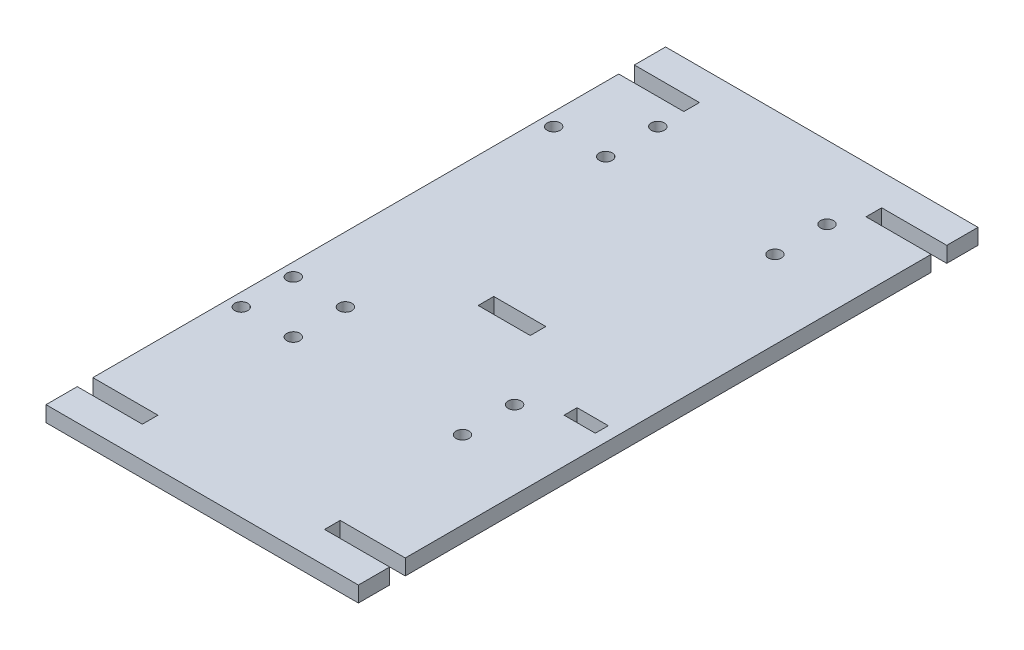
SolidWorks part; units mm, degrees
ref_plane "Front" through (0, 0, 0) normal (0, 0, 1) x (1, 0, 0)
ref_plane "Top" through (0, 0, 0) normal (0, 1, 0) x (1, 0, 0)
ref_plane "Right" through (0, 0, 0) normal (1, 0, 0) x (0, 0, -1)
sketch "Sketch1" plane through (0, 0, 0) normal (0, 1, 0) x (1, 0, 0)
  line L1 (0, 0) -> (-120, 0)
  line L2 (0, 0) -> (0, 238)
  line L3 (0, 238) -> (-120, 238)
  line L4 (-120, 0) -> (-120, 238)
  dimension "D1" = 238
  dimension "D2" = 120
extrude "Boss-Extrude1" add sketch "Sketch1" along normal blind 6
sketch "Sketch2" plane through (0, 6, 0) normal (0, 1, 0) x (1, 0, 0)
  line L0 (-120, 238) -> (-120, 0) construction
  line L1 (-120, 226) -> (-95, 226)
  line L2 (-120, 226) -> (-120, 220)
  line L3 (-120, 220) -> (-95, 220)
  line L4 (-95, 226) -> (-95, 220)
  line L5 (0, 238) -> (-120, 238) construction
  dimension "D1" = 6
  dimension "D2" = 25
  dimension "D3" = 12
extrude "Cut-Extrude1" cut sketch "Sketch2" against normal through all
pattern_linear "LPattern1" count 2 spacing 208 along (0, 0, 1) count 2 spacing 95 along (1, 0, 0) of "Cut-Extrude1"
sketch "Sketch3" plane through (0, 6, 0) normal (0, 1, 0) x (1, 0, 0)
  line L0 (-60, 238) -> (-60, 0) construction
  line L1 (0, 238) -> (-120, 238) construction
  line L2 (-120, 0) -> (0, 0) construction
  line L3 (-120, 119) -> (0, 119) construction
  line L4 (-120, 220) -> (-120, 18) construction
  line L5 (0, 18) -> (0, 220) construction
  line L7 (-70, 116) -> (-50, 116)
  line L8 (-70, 116) -> (-70, 122)
  line L9 (-70, 122) -> (-50, 122)
  line L10 (-50, 116) -> (-50, 122)
  line L11 (-70, 116) -> (-50, 122) construction
  line L12 (-70, 122) -> (-50, 116) construction
  point P12 (-60, 119)
  dimension "D1" = 6
  dimension "D2" = 20
extrude "Cut-Extrude2" cut sketch "Sketch3" against normal blind 10
sketch "Sketch4" plane through (0, 6, 0) normal (0, 1, 0) x (1, 0, 0)
  line L0 (-105, 90) -> (-105, 190) construction
  line L1 (-30, 210) -> (-30, 190) construction
  line L2 (-95, 200) -> (-30, 200) construction
  line L3 (-95, 80) -> (-30, 80) construction
  line L4 (-70, 116) -> (-50, 116) construction
  line L5 (-105, 80) -> (-105, 30) construction
  line L6 (-120, 220) -> (-120, 18) construction
  line L7 (-115, 90) -> (-95, 90) construction
  line L8 (-95, 90) -> (-95, 70) construction
  line L9 (-30, 90) -> (-30, 70) construction
  line L10 (-115, 90) -> (-115, 70) construction
  line L11 (-115, 70) -> (-95, 70) construction
  arc A0 (-105, 90) -> (-95, 80) centre (-95, 90) ccw construction
  arc A1 (-105, 190) -> (-95, 200) centre (-95, 190) cw construction
  circle A2 centre (-30, 210) radius 2.5
  circle A3 centre (-30, 190) radius 2.5
  circle A4 centre (-95, 210) radius 2.5
  circle A5 centre (-95, 190) radius 2.5
  circle A6 centre (-115, 190) radius 2.5
  circle A13 centre (-95, 90) radius 2.5
  circle A14 centre (-115, 90) radius 2.5
  circle A15 centre (-95, 70) radius 2.5
  circle A16 centre (-30, 90) radius 2.5
  circle A17 centre (-30, 70) radius 2.5
  circle A18 centre (-115, 70) radius 2.5
  point P11 (-120, 119)
  point P15 (-105, 200)
  point P17 (-95, 200)
  point P18 (-105, 190)
  point P19 (-105, 90)
  point P20 (-95, 80)
  point P21 (-30, 80)
  point P23 (-30, 200)
  point P26 (-95, 80)
  point P32 (-105, 90)
  point P35 (-95, 190)
  point P39 (-30, 80)
  dimension "D6" = 10
  dimension "D7" = 5
  dimension "D1" = 36
  dimension "D2" = 50
  dimension "D3" = 75
  dimension "D4" = 15
  dimension "D5" = 120
  dimension "D8" = 20
  dimension "D9" = 2
  dimension "D10" = 2
extrude "Cut-Extrude4" cut sketch "Sketch4" against normal blind 10
sketch "Sketch6" plane through (0, 6, 0) normal (0, 1, 0) x (1, 0, 0)
  line L0 (0, 18) -> (0, 220) construction
  line L1 (-5, 101) -> (-17, 101)
  line L2 (-5, 101) -> (-5, 96)
  line L3 (-5, 96) -> (-17, 96)
  line L4 (-17, 101) -> (-17, 96)
  line L5 (-70, 116) -> (-50, 116) construction
  dimension "D1" = 5
  dimension "D2" = 12
  dimension "D3" = 5
  dimension "D4" = 15
extrude "Cut-Extrude5" cut sketch "Sketch6" against normal blind 10
